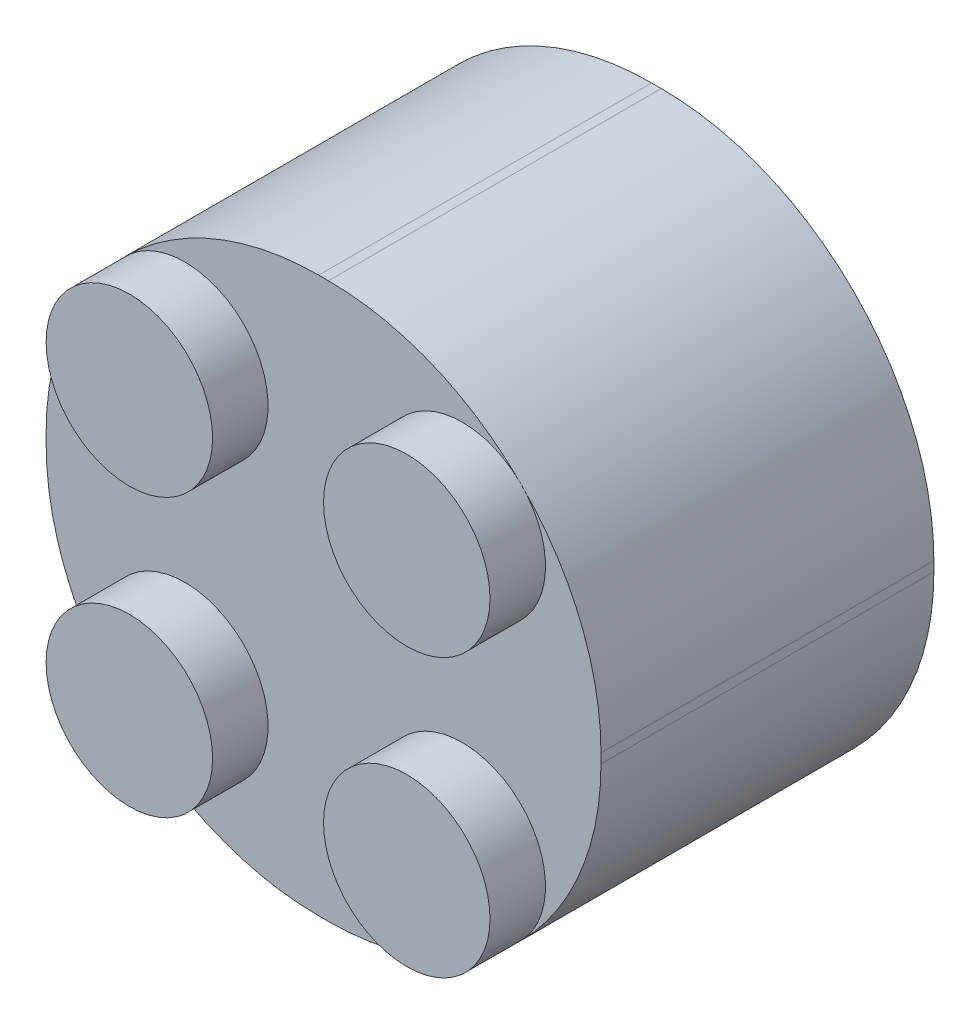
SolidWorks part; units mm, degrees
ref_plane "Front Plane" through (0, 0, 0) normal (0, 0, 1) x (1, 0, 0)
ref_plane "Top Plane" through (0, 0, 0) normal (0, 1, 0) x (1, 0, 0)
ref_plane "Right Plane" through (0, 0, 0) normal (1, 0, 0) x (0, 0, -1)
sketch "Sketch1" plane through (0, 0, 0) normal (0, 0, 1) x (1, 0, 0)
  line L1 (0, 0) -> (16, 0)
  line L2 (0, 0) -> (0, 16)
  line L3 (0, 16) -> (16, 16)
  line L4 (16, 0) -> (16, 16)
  dimension "D1" = 16
  dimension "D2" = 16
extrude "Boss-Extrude1" add sketch "Sketch1" along normal blind 9.6
sketch "Sketch2" plane through (0, 0, 9.6) normal (0, 0, 1) x (1, 0, 0)
  line L0 (16, 16) -> (0, 16) construction
  line L1 (0, 16) -> (0, 0) construction
  circle A0 centre (4, 12) radius 2.4
  dimension "D1" = 4.8
  dimension "D2" = 4
  dimension "D3" = 4
extrude "Boss-Extrude2" add sketch "Sketch2" along normal blind 1.6
pattern_linear "LPattern1" count 2 spacing 8 along (1, 0, 0) count 2 spacing 8 along (0, -1, 0) of "Boss-Extrude2"
fillet "Fillet1" radius 7.86 4 edges at (16, 16, 4.8) (16, 0, 4.8) (0, 0, 4.8) (0, 16, 4.8)
shell "Shell1" thickness 1.6
sketch "Sketch3" plane through (0, 0, 8) normal (0, 0, -1) x (-1, 0, 0)
  circle A0 centre (-8, 8) radius 2.4
  circle A1 centre (-4, 4) radius 0.8 construction
  circle A3 centre (-12, 4) radius 0.8 construction
  circle A4 centre (-8, 8) radius 3.256
  dimension "D2" = 5.6569
  dimension "D3" = 4.8
  dimension "D4" = 6.512
  dimension "D1" = 5.6569
extrude "Boss-Extrude3" add sketch "Sketch3" along normal blind 8
